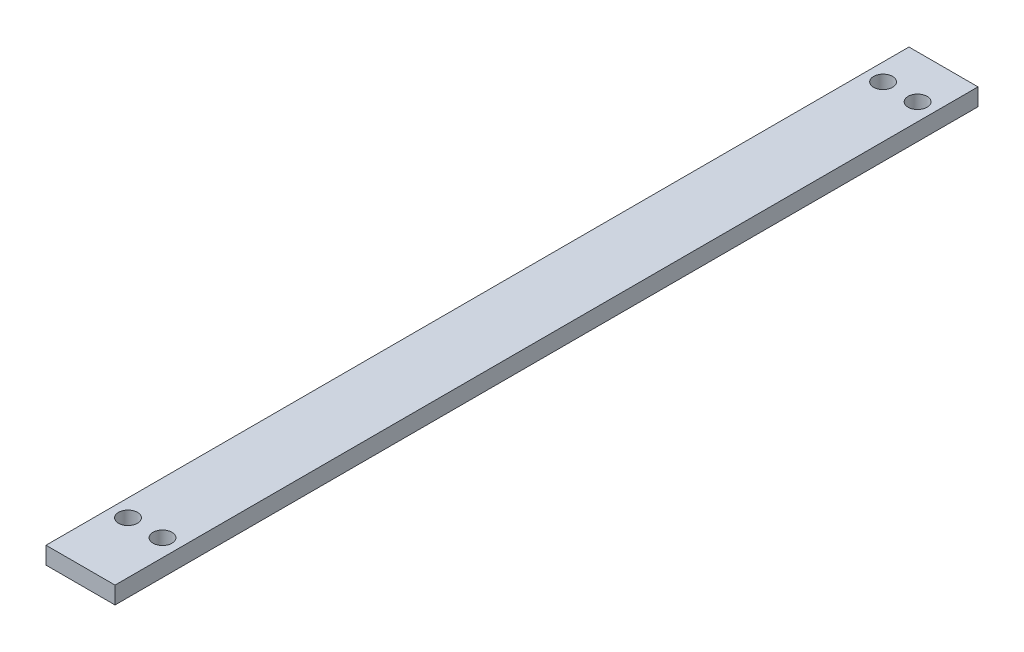
SolidWorks part; units mm, degrees
ref_plane "前视基准面" through (0, 0, 0) normal (0, 0, 1) x (1, 0, 0)
ref_plane "上视基准面" through (0, 0, 0) normal (0, 1, 0) x (1, 0, 0)
ref_plane "右视基准面" through (0, 0, 0) normal (1, 0, 0) x (0, 0, -1)
sketch "草图1" plane through (0, 0, 0) normal (0, 1, 0) x (1, 0, 0)
  line L0 (0, 0) -> (16, 0)
  line L1 (0, 0) -> (0, 200)
  line L2 (16, 0) -> (16, 200)
  line L3 (0, 200) -> (16, 200)
  line L4 (8, 0) -> (8, 15)
  line L7 (8, 15) -> (4, 15)
  line L8 (4, 15) -> (8, 15)
  line L9 (8, 15) -> (12, 15)
  circle A0 centre (12, 190) radius 2.2
  circle A1 centre (4, 190) radius 2.2
  circle A2 centre (4, 15) radius 2.2
  circle A3 centre (12, 15) radius 2.2
extrude "凸台-拉伸1" add sketch "草图1" along normal blind 4
